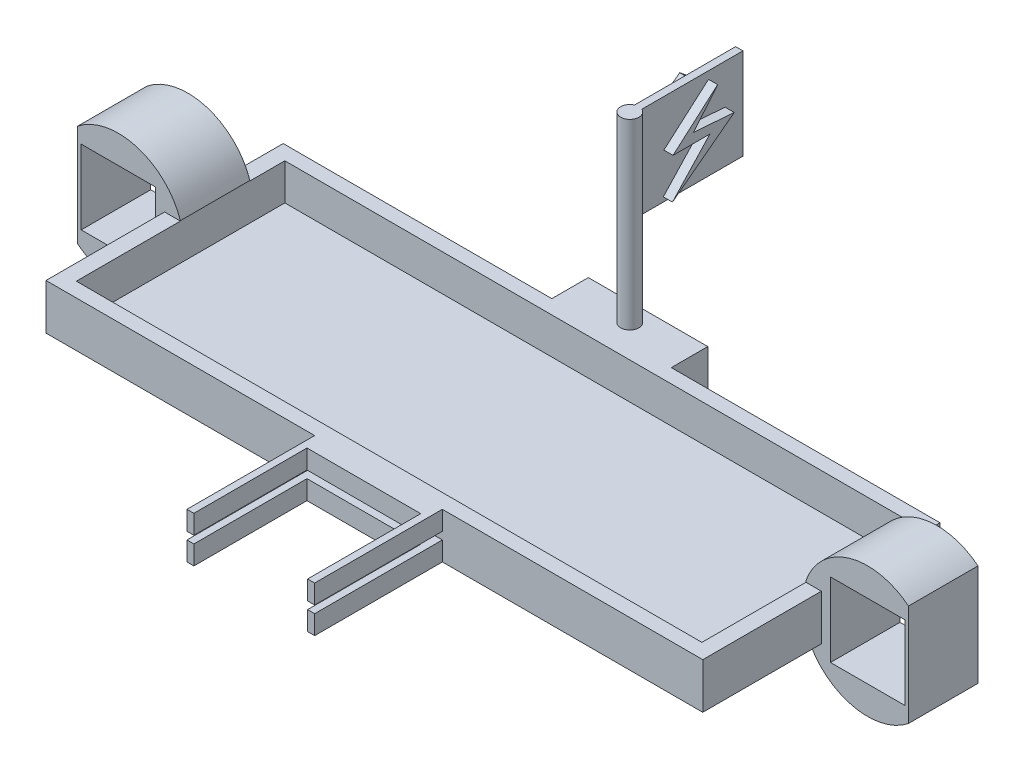
SolidWorks part; units mm, degrees
ref_plane "Front Plane" through (0, 0, 0) normal (0, 0, 1) x (1, 0, 0)
ref_plane "Top Plane" through (0, 0, 0) normal (0, 1, 0) x (1, 0, 0)
ref_plane "Right Plane" through (0, 0, 0) normal (1, 0, 0) x (0, 0, -1)
sketch "Sketch1" plane through (0, 0, 0) normal (0, 1, 0) x (1, 0, 0)
  line L1 (0, 0) -> (171.45, 0)
  line L2 (0, 0) -> (0, 57.15)
  line L3 (0, 57.15) -> (171.45, 57.15)
  line L4 (171.45, 0) -> (171.45, 57.15)
  line L5 (-4.3258, -3.9828) -> (175.6742, -3.9828)
  line L6 (-4.3258, -3.9828) -> (-4.3258, 61.0172)
  line L7 (-4.3258, 61.0172) -> (175.6742, 61.0172)
  line L8 (175.6742, -3.9828) -> (175.6742, 61.0172)
  line L9 (-4.3258, -3.9828) -> (175.6742, 61.0172) construction
  line L10 (-4.3258, 61.0172) -> (175.6742, -3.9828) construction
  point P5 (85.6742, 28.5172)
extrude "Boss-Extrude1" add sketch "Sketch1" along normal blind 10
sketch "Sketch2" plane through (0, 0, 0) normal (0, -1, 0) x (-1, 0, 0)
  line L1 (4.3258, -3.9828) -> (-175.6742, -3.9828)
  line L2 (4.3258, -3.9828) -> (4.3258, 61.0172)
  line L3 (4.3258, 61.0172) -> (-175.6742, 61.0172)
  line L4 (-175.6742, -3.9828) -> (-175.6742, 61.0172)
extrude "Boss-Extrude2" add sketch "Sketch2" along normal blind 2.5
sketch "Sketch3" plane through (175.6742, 0, 0) normal (1, 0, 0) x (0, 0, -1)
  line L0 (28.5172, 3.75) -> (28.5172, 14.6477)
  line L2 (28.5172, 14.6477) -> (47.5672, 14.6477)
  line L3 (28.5172, 14.6477) -> (28.5172, -5.6723)
  line L4 (28.5172, -5.6723) -> (47.5672, -5.6723)
  line L5 (47.5672, 14.6477) -> (47.5672, -5.6723)
  line M5 (-3.9828, -2.5) -> (61.0172, -2.5)
  line M7 (61.0172, 10) -> (-3.9828, 10)
extrude "Boss-Extrude3" add sketch "Sketch3" along normal blind 2.5 contours L5 L2 L0 M7 | L5 L0 L3 M7 M5 | L5 L3 L4 M5
sketch "Sketch4" plane through (0, 0, -47.5672) normal (0, 0, -1) x (-1, 0, 0)
  line L0 (-200.9942, 14.6477) -> (-198.5536, 14.6477)
  line L1 (-175.6742, -5.6723) -> (-200.9942, -5.6723)
  line L2 (-175.6742, -5.6723) -> (-175.6742, 14.6477)
  line L3 (-175.6742, 14.6477) -> (-200.9942, 14.6477)
  line L4 (-200.9942, -5.6723) -> (-200.9942, 14.6477)
  line L5 (-198.5536, 14.6477) -> (-198.5536, -5.6723)
  line L7 (-200.9942, -5.6723) -> (-175.6742, -5.6723)
  line L8 (-200.9942, -5.6723) -> (-200.9942, -8.1721)
  line L9 (-200.9942, -8.1721) -> (-175.6742, -8.1721)
  line L10 (-175.6742, -5.6723) -> (-175.6742, -8.1721)
  line L11 (-200.9942, 14.6477) -> (-175.6742, 14.6477)
  line L12 (-200.9942, 14.6477) -> (-200.9942, 17.1265)
  line L13 (-200.9942, 17.1265) -> (-175.6742, 17.1265)
  line L14 (-175.6742, 14.6477) -> (-175.6742, 17.1265)
  line M4 (-175.6742, 14.6477) -> (-178.1742, 14.6477)
  line M6 (-178.1742, -5.6723) -> (-175.6742, -5.6723)
extrude "Boss-Extrude4" add sketch "Sketch4" against normal up to surface (19.05 mm away) contours L14 L13 L12 L0 L3 M4 | L5 L0 L4 L1 | L10 L1 L8 L9 M6 up to face at (176.5076, 4.2418, -28.5172)
sketch "Sketch5" plane through (-4.3258, 0, 0) normal (-1, 0, 0) x (0, 0, 1)
  line L1 (-47.5672, 17.1265) -> (-28.5172, 17.1265)
  line L2 (-47.5672, 17.1265) -> (-47.5672, -8.1721)
  line L3 (-47.5672, -8.1721) -> (-28.5172, -8.1721)
  line L4 (-28.5172, 17.1265) -> (-28.5172, -8.1721)
extrude "Boss-Extrude5" add sketch "Sketch5" along normal blind 2.5
sketch "Sketch6" plane through (0, 0, -28.5172) normal (0, 0, 1) x (1, 0, 0)
  line L0 (-4.3258, 14.6477) -> (-26.5258, 14.6477)
  line L2 (-4.3258, -8.1721) -> (-4.3258, 14.6822)
  line L3 (-4.3258, 14.6822) -> (-29.6458, 14.6822)
  line L4 (-29.6458, -8.1721) -> (-29.6458, 14.6822)
  line L5 (-29.6458, 14.6822) -> (-27.1719, 14.6822)
  line L6 (-29.6458, 14.6822) -> (-29.6458, -8.1721)
  line L7 (-29.6458, -8.1721) -> (-27.1719, -8.1721)
  line L8 (-27.1719, 14.6822) -> (-27.1719, -8.1721)
  line L13 (-4.3258, 14.6822) -> (-29.6458, 14.6822)
  line L14 (-4.3258, 14.6822) -> (-4.3258, 17.1157)
  line L15 (-4.3258, 17.1157) -> (-29.6458, 17.1157)
  line L16 (-29.6458, 14.6822) -> (-29.6458, 17.1157)
  line L17 (-4.3258, -5.6723) -> (-27.1719, -5.6723)
  line L19 (-29.6458, -5.6723) -> (-4.3258, -5.6723)
  line L20 (-29.6458, -5.6723) -> (-29.6458, -8.1721)
  line L21 (-29.6458, -8.1721) -> (-4.3258, -8.1721)
  line L22 (-4.3258, -5.6723) -> (-4.3258, -8.1721)
extrude "Boss-Extrude6" add sketch "Sketch6" against normal up to surface (19.05 mm away) up to face at (-5.1591, 4.2348, -47.5672)
sketch "Sketch7" plane through (0, 0, 3.9828) normal (0, 0, 1) x (1, 0, 0)
  line L0 (-4.3258, 10) -> (175.6742, 10) construction
  line L1 (69.3017, -2.5) -> (104.3017, -2.5)
  line L2 (69.3017, -2.5) -> (69.3017, 10)
  line L3 (69.3017, 10) -> (104.3017, 10)
  line L4 (104.3017, -2.5) -> (104.3017, 10)
  line L5 (69.3017, -2.5) -> (104.3017, 10) construction
  line L6 (69.3017, 10) -> (104.3017, -2.5) construction
  line L8 (69.3017, 2.7236) -> (104.3017, 2.7236)
  line L9 (69.3017, 2.7236) -> (69.3017, 4.7764)
  line L10 (69.3017, 4.7764) -> (104.3017, 4.7764)
  line L11 (104.3017, 2.7236) -> (104.3017, 4.7764)
  line L12 (69.3017, 2.7236) -> (104.3017, 4.7764) construction
  line L13 (69.3017, 4.7764) -> (104.3017, 2.7236) construction
  point P0 (86.8017, 3.75)
  point P7 (86.8017, 3.75)
  line M3 (-4.3258, -2.5) -> (175.6742, -2.5)
  line M5 (175.6742, 10) -> (-4.3258, 10)
extrude "Boss-Extrude7" add sketch "Sketch7" along normal blind 4 contours L2 L10 L4 M5 | L8 L2 L4 M3
sketch "Sketch8" plane through (0, 0, 3.9828) normal (0, 0, 1) x (1, 0, 0)
  line L0 (104.3017, 10) -> (69.3017, 10) construction
  line L1 (69.3017, 4.7764) -> (71.2017, 4.7764)
  line L2 (69.3017, 4.7764) -> (69.3017, 10)
  line L3 (69.3017, 10) -> (71.2017, 10)
  line L4 (71.2017, 4.7764) -> (71.2017, 10)
  line L5 (69.3017, -2.5) -> (104.3017, -2.5) construction
  line L6 (69.3017, 2.7236) -> (71.2017, 2.7236)
  line L7 (69.3017, 2.7236) -> (69.3017, -2.5)
  line L8 (69.3017, -2.5) -> (71.2017, -2.5)
  line L9 (71.2017, 2.7236) -> (71.2017, -2.5)
  line L10 (69.3017, 2.7236) -> (104.3017, 2.7236) construction
  line L11 (104.3017, -2.5) -> (102.3679, -2.5)
  line L12 (104.3017, -2.5) -> (104.3017, 2.7236)
  line L13 (104.3017, 2.7236) -> (102.3679, 2.7236)
  line L14 (102.3679, -2.5) -> (102.3679, 2.7236)
  line L16 (104.3017, 4.7764) -> (102.3679, 4.7764)
  line L17 (104.3017, 4.7764) -> (104.3017, 10)
  line L18 (104.3017, 10) -> (102.3679, 10)
  line L19 (102.3679, 4.7764) -> (102.3679, 10)
extrude "Boss-Extrude8" add sketch "Sketch8" along normal blind 35
sketch "Sketch9" plane through (0, 0, -28.5172) normal (0, 0, 1) x (1, 0, 0)
  line L0 (-4.3258, -8.1721) -> (-4.3258, -2.5) construction
  line L1 (-29.6458, -8.1721) -> (-4.3258, -8.1721)
  line L2 (-29.6458, -8.1721) -> (-29.6458, -5.6701)
  line L3 (-29.6458, -5.6701) -> (-4.3258, -5.6701)
  line L4 (-4.3258, -8.1721) -> (-4.3258, -5.6701)
extrude "Boss-Extrude9" add sketch "Sketch9" against normal up to surface (19.05 mm away) up to face at (-13.1868, 6.055, -47.5672)
sketch "Sketch10" plane through (0, 0, -28.5172) normal (0, 0, 1) x (1, 0, 0)
  line L0 (0, -8.6966) -> (0, -21.3191)
  line L1 (-27.1719, 14.6822) -> (-6.8258, 14.6822)
  line L2 (-27.1719, 14.6822) -> (-27.1719, -5.6701)
  line L3 (-27.1719, -5.6701) -> (-6.8258, -5.6701)
  line L4 (-6.8258, 14.6822) -> (-6.8258, -5.6701)
  line L5 (178.1742, 14.6477) -> (198.5536, 14.6477)
  line L6 (178.1742, 14.6477) -> (178.1742, -5.6723)
  line L7 (178.1742, -5.6723) -> (198.5536, -5.6723)
  line L8 (198.5536, 14.6477) -> (198.5536, -5.6723)
  line L9 (0, -8.6966) -> (0, 16.593)
  line L10 (171.45, 10) -> (171.45, 13.4763)
  line L11 (171.45, 10) -> (171.45, -21.8256)
  circle A0 centre (-16.9804, 4.4772) radius 17.8926
  circle A1 centre (188.3342, 4.4772) radius 17.8964
  line M3 (-6.8258, -5.6701) -> (-27.1719, -5.6701)
  line M4 (-27.1719, -5.6701) -> (-27.1719, 14.6822)
  line M5 (-27.1719, 14.6822) -> (-6.8258, 14.6822)
  line M6 (-6.8258, 14.6822) -> (-6.8258, -5.6701)
  line M7 (-6.8258, 17.1157) -> (-29.6458, 17.1157)
  line M8 (-29.6458, 17.1157) -> (-29.6458, -8.1721)
  line M9 (-29.6458, -8.1721) -> (-4.3258, -8.1721)
  line M10 (-4.3258, -8.1721) -> (-4.3258, -2.5)
  line M11 (-4.3258, -2.5) -> (-4.3258, 10)
  line M12 (-4.3258, 10) -> (-4.3258, 17.1265)
  line M13 (-4.3258, 17.1265) -> (-6.8258, 17.1265)
  line M14 (-6.8258, 17.1265) -> (-6.8258, 17.1157)
extrude "Boss-Extrude10" add sketch "Sketch10" along direction (0, 0, 1) on the side against the normal up to surface (19.05 mm away) contours A0 M13 M7 M14 | A0 M8 M9 M10 M11 M12 M13 M14 M7 M6 M3 M4 M5 | L9 A0 M12 M11 M10 | A0 M9 | A0 M8 | L11 A1 L10 L5 L8 L7 L6
sketch "Sketch11" plane through (0, 0, -28.5172) normal (0, 0, 1) x (1, 0, 0)
  line L0 (-27.1719, 4.5061) -> (-28.1719, 4.5061)
  line L1 (-27.1719, 14.6822) -> (-27.1719, -5.6701) construction
  line L2 (198.5536, 4.4877) -> (199.5536, 4.4877)
  line L3 (-28.1719, 4.5061) -> (-53.1735, 4.5061)
  line L4 (-28.1719, 4.5061) -> (-28.1719, -18.4576)
  line L5 (-28.1719, -18.4576) -> (-53.1735, -18.4576)
  line L6 (-53.1735, 4.5061) -> (-53.1735, -18.4576)
  line L7 (-28.1719, 4.5061) -> (-53.381, 4.5061)
  line L8 (-28.1719, 4.5061) -> (-28.1719, 29.6715)
  line L9 (-28.1719, 29.6715) -> (-53.381, 29.6715)
  line L10 (-53.381, 4.5061) -> (-53.381, 29.6715)
  line L11 (198.5536, 14.6477) -> (198.5536, -5.6723) construction
  line L13 (199.5536, 4.4877) -> (220.6074, 4.4877)
  line L14 (199.5536, 4.4877) -> (199.5536, 30.731)
  line L15 (199.5536, 30.731) -> (220.6074, 30.731)
  line L16 (220.6074, 4.4877) -> (220.6074, 30.731)
  line L17 (199.5536, 4.4877) -> (220.206, 4.4877)
  line L18 (199.5536, 4.4877) -> (199.5536, -22.6635)
  line L19 (199.5536, -22.6635) -> (220.206, -22.6635)
  line L20 (220.206, 4.4877) -> (220.206, -22.6635)
  line M2 (-29.6458, -8.1721) -> (-29.635, -8.1721)
  arc M3 (-29.635, -8.1721) -> (-0.5043, -2.5) centre (-16.9804, 4.4772) ccw
  arc M8 (0, 10.1173) -> (-29.6458, -8.1613) centre (-16.9804, 4.4772) ccw
  line M9 (-29.6458, -8.1613) -> (-29.6458, -8.1721)
extrude "Cut-Extrude1" cut sketch "Sketch11" against normal through all contours L10 L7 L3 L8 L9 M8 | L3 L6 L5 L4 M3 M2 M9 M8 | L3 L8 M8 | L4 L3 M8 M9 M2 M3 | L13 L16 L15 L14 | L20 L13 L18 L19
sketch "Sketch12" plane through (0, 0, -61.0172) normal (0, 0, -1) x (-1, 0, 0)
  line L1 (-102.0468, -2.5) -> (-69.3017, -2.5)
  line L2 (-102.0468, -2.5) -> (-102.0468, 10)
  line L3 (-102.0468, 10) -> (-69.3017, 10)
  line L4 (-69.3017, -2.5) -> (-69.3017, 10)
  line L5 (-102.0468, -2.5) -> (-69.3017, 10) construction
  line L6 (-102.0468, 10) -> (-69.3017, -2.5) construction
  point P0 (-85.6742, 3.75)
extrude "Boss-Extrude11" add sketch "Sketch12" along normal blind 10
sketch "Sketch13" plane through (0, 10, 0) normal (0, 1, 0) x (1, 0, 0)
  circle A0 centre (85.6742, 66.0172) radius 2.5
extrude "Boss-Extrude12" add sketch "Sketch13" along normal blind 50
sketch "Sketch14" plane through (0, 60, 0) normal (0, 1, 0) x (1, 0, 0)
  line L0 (83.1742, 66.0172) -> (88.1742, 66.0172)
  line L1 (84.6742, 36.0172) -> (86.6742, 36.0172)
  line L2 (84.6742, 36.0172) -> (84.6742, 96.0172)
  line L3 (84.6742, 96.0172) -> (86.6742, 96.0172)
  line L4 (86.6742, 36.0172) -> (86.6742, 96.0172)
  line L5 (84.6742, 36.0172) -> (86.6742, 96.0172) construction
  line L6 (84.6742, 96.0172) -> (86.6742, 36.0172) construction
  circle A0 centre (85.6742, 66.0172) radius 2.5 construction
  circle A1 centre (85.6742, 66.0172) radius 2.5 construction
  point P0 (85.6742, 66.0172)
  circle M3 centre (85.6742, 66.0172) radius 2.5
extrude "Boss-Extrude13" add sketch "Sketch14" against normal blind 25 contours L0 L4 L2 M3 | L4 L3 L2 M3
sketch "Sketch15" plane through (86.6742, 0, 0) normal (1, 0, 0) x (0, 0, -1)
  line L0 (86.5901, 57.9492) -> (74.3645, 47.2746)
  line L1 (74.3645, 47.2746) -> (84.463, 47.2746)
  line L2 (84.463, 47.2746) -> (74.2057, 36.2416)
  line L3 (74.2057, 36.2416) -> (91.1434, 49.0659)
  line L4 (91.1434, 49.0659) -> (80.0207, 49.9091)
  line L5 (80.0207, 49.9091) -> (86.5901, 57.9492)
extrude "Boss-Extrude14" add sketch "Sketch15" along normal blind 2.5
sketch "Sketch16" plane through (84.6742, 0, 0) normal (-1, 0, 0) x (0, 0, 1)
  line L0 (-88.8314, 54.4807) -> (-88.8314, 49.4807)
  line L1 (-83.2078, 54.4807) -> (-83.2078, 49.4807)
  line L2 (-77.0085, 54.4807) -> (-77.0085, 49.4807)
  line L3 (-88.8314, 46.2445) -> (-88.8314, 41.2445)
  line L4 (-83.2078, 46.2445) -> (-83.2078, 41.2445)
  line L5 (-77.0085, 46.2445) -> (-77.0085, 41.2445)
  line L6 (-83.2078, 49.4807) -> (-77.0085, 46.2445)
  line L7 (-88.8314, 49.4807) -> (-83.2078, 46.2445)
  line L8 (-88.8314, 46.2445) -> (-83.2078, 41.2445)
  line L9 (-83.2078, 54.4807) -> (-77.0085, 49.4807)
  line L10 (-88.8314, 54.4807) -> (-83.2078, 58.9567)
  line L11 (-83.2078, 58.9567) -> (-77.0085, 54.4807)
  line L12 (-88.8314, 41.2445) -> (-83.3201, 36.7994)
  line L13 (-83.3201, 36.7994) -> (-77.0085, 41.2445)
extrude "Boss-Extrude15" add sketch "Sketch16" along normal blind 2.5
